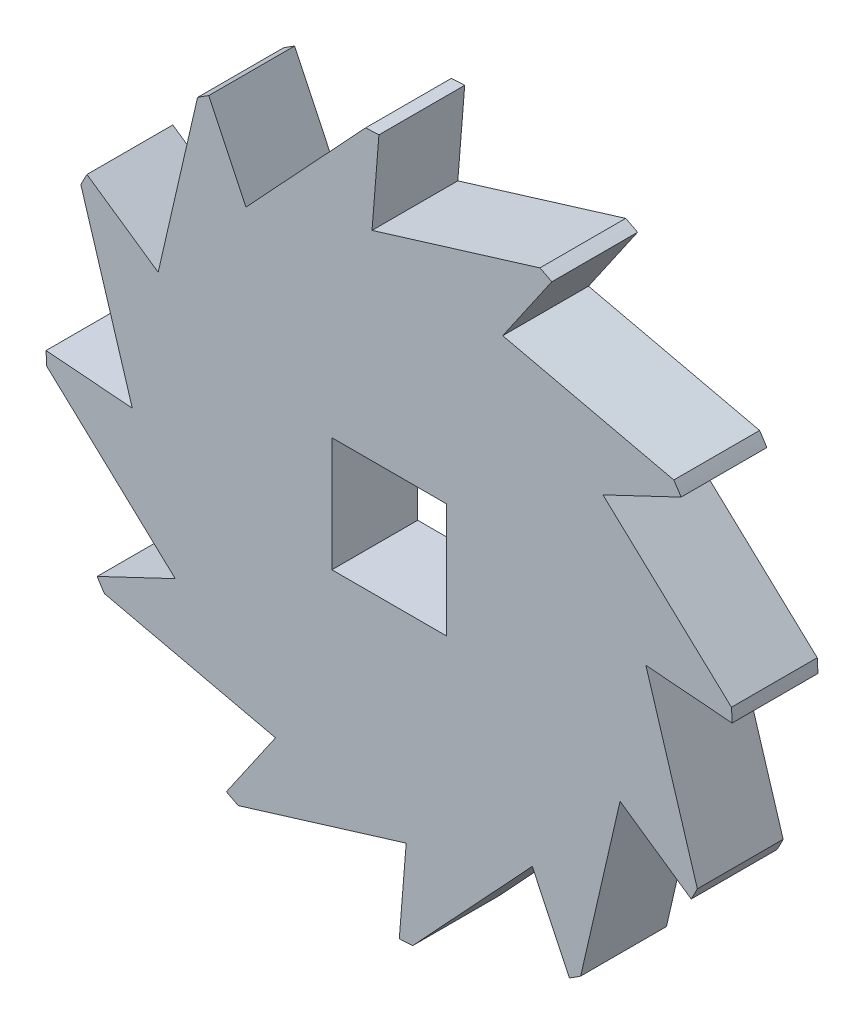
SolidWorks part; units mm, degrees
ref_plane "Front Plane" through (0, 0, 0) normal (0, 0, 1) x (1, 0, 0)
ref_plane "Top Plane" through (0, 0, 0) normal (0, 1, 0) x (1, 0, 0)
ref_plane "Right Plane" through (0, 0, 0) normal (1, 0, 0) x (0, 0, -1)
sketch "Sketch1" plane through (0, 0, 0) normal (0, 0, 1) x (1, 0, 0)
  line L0 (-5, 5) -> (-5, 22.45) construction
  line L1 (-5, -5) -> (5, -5)
  line L2 (-5, -5) -> (-5, 5)
  line L3 (-5, 5) -> (5, 5)
  line L4 (5, -5) -> (5, 5)
  line L5 (-5, -5) -> (5, 5) construction
  line L6 (-5, 5) -> (5, -5) construction
  line L7 (-5, 22.45) -> (-0.89, 22.45) construction
  line L8 (9.9314, 20.1891) -> (24.8909, 16.7465)
  line L9 (14.2226, 26.4143) -> (9.9314, 20.1891)
  line L10 (-0.89, 29.9868) -> (-1.4937, 22.45)
  line L11 (-1.4937, 22.45) -> (13.1829, 26.9483)
  line L12 (18.6954, 12.5186) -> (29.9294, 2.0574)
  line L13 (25.5243, 15.7642) -> (18.6954, 12.5186)
  line L14 (22.45, 1.4937) -> (26.9483, -13.1829)
  line L15 (29.9868, 0.89) -> (22.45, 1.4937)
  line L16 (20.1891, -9.9314) -> (16.7465, -24.8909)
  line L17 (26.4143, -14.2226) -> (20.1891, -9.9314)
  line L18 (12.5186, -18.6954) -> (2.0574, -29.9294)
  line L19 (15.7642, -25.5243) -> (12.5186, -18.6954)
  line L20 (1.4937, -22.45) -> (-13.1829, -26.9483)
  line L21 (0.89, -29.9868) -> (1.4937, -22.45)
  line L22 (-9.9314, -20.1891) -> (-24.8909, -16.7465)
  line L23 (-14.2226, -26.4143) -> (-9.9314, -20.1891)
  line L24 (-18.6954, -12.5186) -> (-29.9294, -2.0574)
  line L25 (-25.5243, -15.7642) -> (-18.6954, -12.5186)
  line L26 (-22.45, -1.4937) -> (-26.9483, 13.1829)
  line L27 (-29.9868, -0.89) -> (-22.45, -1.4937)
  line L28 (-20.1891, 9.9314) -> (-16.7465, 24.8909)
  line L29 (-26.4143, 14.2226) -> (-20.1891, 9.9314)
  line L30 (-12.5186, 18.6954) -> (-2.0574, 29.9294)
  line L31 (-15.7642, 25.5243) -> (-12.5186, 18.6954)
  arc A0 (-15.7642, 25.5243) -> (-16.7465, 24.8909) centre (0, 0) ccw
  arc A1 (-0.89, 29.9868) -> (-2.0574, 29.9294) centre (0, 0) ccw
  arc A2 (14.2226, 26.4143) -> (13.1829, 26.9483) centre (0, 0) ccw
  arc A3 (25.5243, 15.7642) -> (24.8909, 16.7465) centre (0, 0) ccw
  arc A4 (29.9868, 0.89) -> (29.9294, 2.0574) centre (0, 0) ccw
  arc A5 (26.4143, -14.2226) -> (26.9483, -13.1829) centre (0, 0) ccw
  arc A6 (15.7642, -25.5243) -> (16.7465, -24.8909) centre (0, 0) ccw
  arc A7 (0.89, -29.9868) -> (2.0574, -29.9294) centre (0, 0) ccw
  arc A8 (-14.2226, -26.4143) -> (-13.1829, -26.9483) centre (0, 0) ccw
  arc A9 (-25.5243, -15.7642) -> (-24.8909, -16.7465) centre (0, 0) ccw
  arc A10 (-29.9868, -0.89) -> (-29.9294, -2.0574) centre (0, 0) ccw
  arc A11 (-26.4143, 14.2226) -> (-26.9483, 13.1829) centre (0, 0) ccw
  point P48 (0, 0)
  dimension "D1" = 60
  dimension "D2" = 10
  dimension "D3" = 17.45
  dimension "D4" = 4.11
  dimension "D5" = 4.58
  dimension "D6" = 68.38
  dimension "D7" = 12
extrude "Boss-Extrude1" add sketch "Sketch1" along normal blind 7.5
